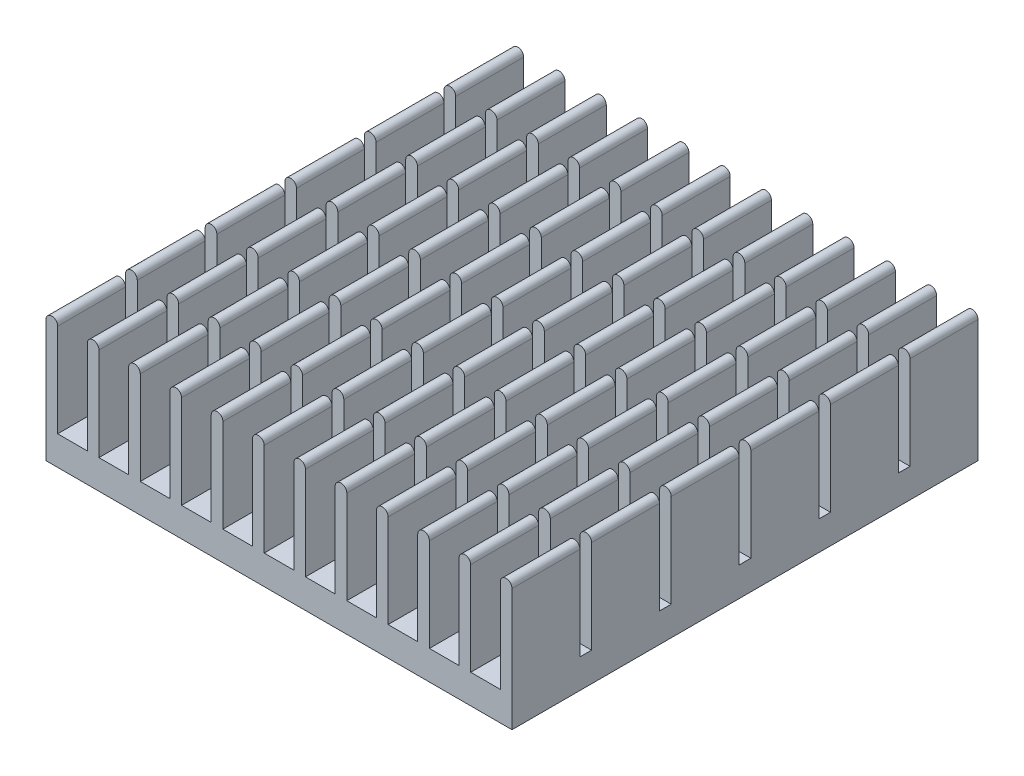
SolidWorks part; units mm, degrees
material "A286 Superalliage à base de fer"
ref_plane "Plan de face" through (0, 0, 0) normal (0, 0, 1) x (1, 0, 0)
ref_plane "Plan de dessus" through (0, 0, 0) normal (0, 1, 0) x (1, 0, 0)
ref_plane "Esquisse1Esquisse1" through (0, 0, 0) normal (1, 0, 0) x (0, 0, -1)
sketch "Esquisse1" plane through (0, 0, 0) normal (0, 0, 1) x (1, 0, 0)
  line L0 (-19, 2.5) -> (-16.4545, 2.5)
  line L2 (-20, 10.5) -> (-20, 0)
  line L3 (-20, 0) -> (20, 0)
  line L4 (20, 11) -> (20, 0)
  line L10 (-20, 10.5) -> (-20, 2.5)
  line L12 (-19, 10.5) -> (-19, 2.5)
  line L13 (-20, 10.5) -> (-19, 10.5) construction
  line L14 (-16.4545, 10.5) -> (-16.4545, 2.5)
  line L15 (-15.4545, 10.5) -> (-15.4545, 2.5)
  line L16 (-16.4545, 10.5) -> (-15.4545, 10.5) construction
  line L17 (-12.9091, 10.5) -> (-12.9091, 2.5)
  line L18 (-11.9091, 10.5) -> (-11.9091, 2.5)
  line L19 (-12.9091, 10.5) -> (-11.9091, 10.5) construction
  line L20 (-9.3636, 10.5) -> (-9.3636, 2.5)
  line L21 (-8.3636, 10.5) -> (-8.3636, 2.5)
  line L22 (-9.3636, 10.5) -> (-8.3636, 10.5) construction
  line L23 (-5.8182, 10.5) -> (-5.8182, 2.5)
  line L24 (-4.8182, 10.5) -> (-4.8182, 2.5)
  line L25 (-5.8182, 10.5) -> (-4.8182, 10.5) construction
  line L26 (-2.2727, 10.5) -> (-2.2727, 2.5)
  line L27 (-1.2727, 10.5) -> (-1.2727, 2.5)
  line L28 (-2.2727, 10.5) -> (-1.2727, 10.5) construction
  line L29 (1.2727, 10.5) -> (1.2727, 2.5)
  line L30 (2.2727, 10.5) -> (2.2727, 2.5)
  line L31 (1.2727, 10.5) -> (2.2727, 10.5) construction
  line L32 (4.8182, 10.5) -> (4.8182, 2.5)
  line L33 (5.8182, 10.5) -> (5.8182, 2.5)
  line L34 (4.8182, 10.5) -> (5.8182, 10.5) construction
  line L35 (8.3636, 10.5) -> (8.3636, 2.5)
  line L36 (9.3636, 10.5) -> (9.3636, 2.5)
  line L37 (8.3636, 10.5) -> (9.3636, 10.5) construction
  line L38 (11.9091, 10.5) -> (11.9091, 2.5)
  line L39 (12.9091, 10.5) -> (12.9091, 2.5)
  line L40 (11.9091, 10.5) -> (12.9091, 10.5) construction
  line L41 (15.4545, 10.5) -> (15.4545, 2.5)
  line L42 (16.4545, 10.5) -> (16.4545, 2.5)
  line L43 (15.4545, 10.5) -> (16.4545, 10.5) construction
  line L44 (19, 10.5) -> (19, 2.5)
  line L45 (20, 10.5) -> (20, 2.5)
  line L46 (19, 10.5) -> (20, 10.5) construction
  line L47 (-11.9091, 2.5) -> (-9.3636, 2.5)
  line L48 (-15.4545, 2.5) -> (-12.9091, 2.5)
  line L49 (-4.8182, 2.5) -> (-2.2727, 2.5)
  line L50 (-8.3636, 2.5) -> (-5.8182, 2.5)
  line L51 (-1.2727, 2.5) -> (1.2727, 2.5)
  line L52 (2.2727, 2.5) -> (4.8182, 2.5)
  line L53 (5.8182, 2.5) -> (8.3636, 2.5)
  line L54 (9.3636, 2.5) -> (11.9091, 2.5)
  line L55 (16.4545, 2.5) -> (19, 2.5)
  line L56 (12.9091, 2.5) -> (15.4545, 2.5)
  line L57 (19.5, 11) -> (20, 11)
  line L58 (-20.487, 11) -> (-17.524, 11) construction
  arc A1 (-20, 10.5) -> (-19, 10.5) centre (-19.5, 10.5) cw
  arc A2 (-16.4545, 10.5) -> (-15.4545, 10.5) centre (-15.9545, 10.5) cw
  arc A3 (-12.9091, 10.5) -> (-11.9091, 10.5) centre (-12.4091, 10.5) cw
  arc A4 (-9.3636, 10.5) -> (-8.3636, 10.5) centre (-8.8636, 10.5) cw
  arc A5 (-5.8182, 10.5) -> (-4.8182, 10.5) centre (-5.3182, 10.5) cw
  arc A6 (-2.2727, 10.5) -> (-1.2727, 10.5) centre (-1.7727, 10.5) cw
  arc A7 (1.2727, 10.5) -> (2.2727, 10.5) centre (1.7727, 10.5) cw
  arc A8 (4.8182, 10.5) -> (5.8182, 10.5) centre (5.3182, 10.5) cw
  arc A9 (8.3636, 10.5) -> (9.3636, 10.5) centre (8.8636, 10.5) cw
  arc A10 (11.9091, 10.5) -> (12.9091, 10.5) centre (12.4091, 10.5) cw
  arc A11 (15.4545, 10.5) -> (16.4545, 10.5) centre (15.9545, 10.5) cw
  arc A12 (19, 10.5) -> (20, 10.5) centre (19.5, 10.5) cw
  dimension "D2" = 11
  dimension "D1" = 40
  dimension "D4" = 2.5
  dimension "D5" = 1
  dimension "D3" = 12
extrude "Boss.-Extru.1" add sketch "Esquisse1" along normal blind 40 contours A12 L44 L55 L42 A11 L41 L56 L39 A10 L38 L54 L36 A9 L35 L53 L33 A8 L32 L52 L30 A7 L29 L51 L27 A6 L26 L49 L24 A5 L23 L50 L21 A4 L20 L47 L18 A3 L17 L48 L15 A2 L14 L0 L12 A1 L2 L3 L4
sketch "Esquisse4" plane through (0, 0, 0) normal (1, 0, 0) x (0, 0, -1)
  line L0 (-40, 2.5) -> (0, 2.5) construction
  line L1 (-27.3333, 2.5) -> (-26.3333, 2.5)
  line L2 (0, 11) -> (-40, 11) construction
  line L4 (-34.1667, 2.5) -> (-34.1667, 11)
  line L5 (-34.1667, 11) -> (-33.1667, 11)
  line L6 (-33.1667, 2.5) -> (-33.1667, 11)
  line L7 (-27.3333, 11) -> (-26.3333, 11)
  line L8 (-27.3333, 2.5) -> (-27.3333, 11)
  line L9 (-26.3333, 2.5) -> (-26.3333, 11)
  line L10 (-20.5, 11) -> (-19.5, 11)
  line L11 (-20.5, 2.5) -> (-20.5, 11)
  line L12 (-19.5, 2.5) -> (-19.5, 11)
  line L13 (-13.6667, 11) -> (-12.6667, 11)
  line L14 (-13.6667, 2.5) -> (-13.6667, 11)
  line L15 (-12.6667, 2.5) -> (-12.6667, 11)
  line L16 (-6.8333, 11) -> (-5.8333, 11)
  line L17 (-6.8333, 2.5) -> (-6.8333, 11)
  line L18 (-5.8333, 2.5) -> (-5.8333, 11)
  line L19 (-20.5, 2.5) -> (-19.5, 2.5)
  line L20 (-13.6667, 2.5) -> (-12.6667, 2.5)
  line L21 (-6.8333, 2.5) -> (-5.8333, 2.5)
  line L22 (-40, 2.5) -> (-34.1667, 2.5) construction
  line L23 (-40, 10.5) -> (-40, 0) construction
  line L24 (-34.1667, 2.5) -> (-33.1667, 2.5)
  line L25 (-27.3333, 2.5) -> (-26.3333, 2.5) construction
  line L26 (-26.3333, 2.5) -> (-20.5, 2.5) construction
  line L27 (-19.5, 2.5) -> (-13.6667, 2.5) construction
  line L28 (-12.6667, 2.5) -> (-6.8333, 2.5) construction
  line L29 (0, 2.5) -> (-5.8333, 2.5) construction
  line L30 (0, 6.05) -> (0, -6.05) construction
  line L31 (-27.3333, 2.5) -> (-33.1667, 2.5) construction
  point P25 (0, 0)
  point P30 (0, 0)
  point P33 (0, 0)
  dimension "D1" = 1
  dimension "D2" = 5
extrude "Enlèv. mat.-Extru.1" cut sketch "Esquisse4" against normal through all both and the other way through all
